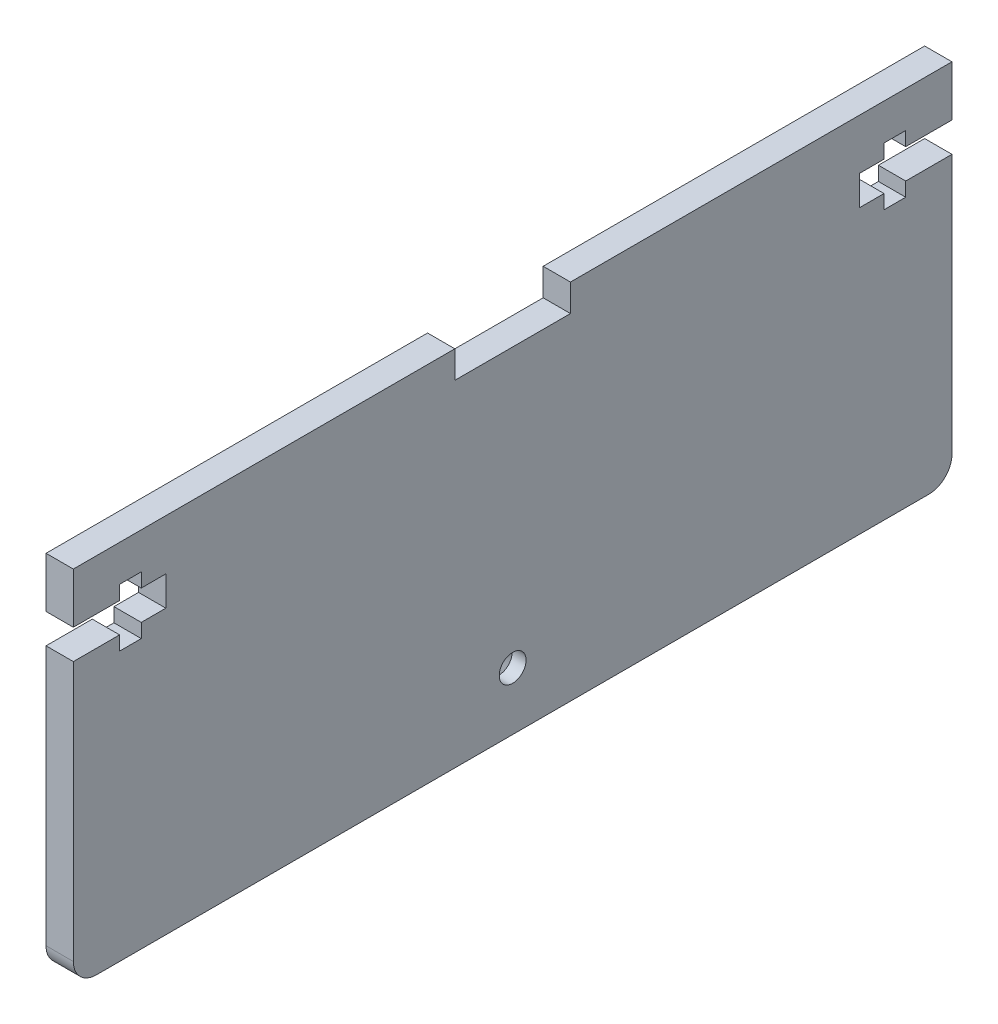
SolidWorks part; units mm, degrees
material "Acrylic (Medium-high impact)"
ref_plane "Front Plane" through (0, 0, 0) normal (0, 0, 1) x (1, 0, 0)
ref_plane "Top Plane" through (0, 0, 0) normal (0, 1, 0) x (1, 0, 0)
ref_plane "Right Plane" through (0, 0, 0) normal (1, 0, 0) x (0, 0, -1)
sketch "Sketch1" plane through (0, 0, 0) normal (1, 0, 0) x (0, 0, -1)
  line L1 (0, 0) -> (96.52, 0)
  line L2 (0, 0) -> (0, 39.878)
  line L3 (0, 39.878) -> (96.52, 39.878)
  line L4 (96.52, 0) -> (96.52, 39.878)
  dimension "D1" = 96.52
  dimension "D2" = 39.878
extrude "Boss-Extrude1" add sketch "Sketch1" along normal blind 3
hole_wizard "#32 (0.116) Diameter Hole1" positions "Sketch3" profile "Sketch2" hole size "#32" standard "ANSI Inch"
sketch "Sketch3" plane through (3, 0, 0) normal (1, 0, 0) x (0, 0, -1)
  line L0 (96.52, 39.878) -> (0, 39.878) construction
  line L1 (96.52, 0) -> (96.52, 39.878) construction
  point P0 (48.26, 6.35)
  dimension "D1" = 33.528
  dimension "D2" = 48.26
sketch "Sketch2" plane through (3, 6.35, -48.26) normal (0, 1, 0) x (0, 0, -1)
  line L0 (0, 0) -> (0, 2.4092)
  line L1 (0, 2.4092) -> (1.4732, 1.524)
  line L2 (1.4732, 1.524) -> (1.4732, 0)
  line L5 (1.4732, 0) -> (0, 0)
  line L10 (0, 2.4092) -> (-1.4732, 1.524) construction
  line L11 (0, -6.35) -> (0, 107.95) construction
  dimension "Hole Dia." = 2.9464
  dimension "Hole Depth" = 1.524
  dimension "Drill Angle" = 118
sketch "Sketch4" plane through (3, 0, 0) normal (1, 0, 0) x (0, 0, -1)
  line L0 (0, 34.338) -> (5.08, 34.338)
  line L1 (0, 39.878) -> (0, 0) construction
  line L2 (5.08, 34.338) -> (5.08, 35.8811)
  line L3 (5.08, 35.8811) -> (7.4613, 35.8811)
  line L4 (7.4613, 35.8811) -> (7.4613, 34.338)
  line L5 (7.4613, 34.338) -> (10.16, 34.338)
  line L6 (10.16, 34.338) -> (10.16, 31.0741)
  line L7 (10.16, 31.0741) -> (7.4613, 31.0741)
  line L8 (7.4613, 31.0741) -> (7.4613, 29.5311)
  line L9 (7.4613, 29.5311) -> (5.08, 29.5311)
  line L10 (5.08, 29.5311) -> (5.08, 31.0741)
  line L11 (5.08, 31.0741) -> (0, 31.0741)
  line L12 (0, 31.0741) -> (0, 34.338)
  line L13 (48.26, 39.878) -> (48.26, 0) construction
  line L14 (96.52, 39.878) -> (0, 39.878) construction
  line L15 (0, 0) -> (96.52, 0) construction
  line L16 (96.52, 31.0741) -> (96.52, 34.338)
  line L17 (91.44, 31.0741) -> (96.52, 31.0741)
  line L18 (91.44, 29.5311) -> (91.44, 31.0741)
  line L19 (89.0587, 29.5311) -> (91.44, 29.5311)
  line L20 (89.0587, 31.0741) -> (89.0587, 29.5311)
  line L21 (86.36, 31.0741) -> (89.0587, 31.0741)
  line L22 (86.36, 34.338) -> (86.36, 31.0741)
  line L23 (89.0587, 34.338) -> (86.36, 34.338)
  line L24 (89.0587, 35.8811) -> (89.0587, 34.338)
  line L25 (91.44, 35.8811) -> (89.0587, 35.8811)
  line L26 (91.44, 34.338) -> (91.44, 35.8811)
  line L27 (96.52, 34.338) -> (91.44, 34.338)
  dimension "D1" = 2.3813
  dimension "D2" = 3.2639
  dimension "D3" = 10.16
  dimension "D4" = 5.08
  dimension "D5" = 6.35
  dimension "D6" = 5.54
extrude "Cut-Extrude1" cut sketch "Sketch4" against normal blind 3
fillet "Fillet1" radius 2.54 2 edges at (1.5, 0, -96.52) (1.5, 0, 0)
sketch "Sketch5" plane through (3, 0, 0) normal (1, 0, 0) x (0, 0, -1)
  line L1 (96.52, 39.878) -> (0, 39.878) construction
  line L2 (41.91, 39.878) -> (54.61, 39.878)
  line L3 (41.91, 39.878) -> (41.91, 36.878)
  line L4 (41.91, 36.878) -> (54.61, 36.878)
  line L6 (54.61, 39.878) -> (54.61, 36.878)
  line L8 (96.52, 34.338) -> (96.52, 39.878) construction
  dimension "D1" = 12.7
  dimension "D2" = 3
  dimension "D3" = 41.91
extrude "Cut-Extrude2" cut sketch "Sketch5" against normal blind 3
sketch "Sketch7" plane through (3, 0, 0) normal (1, 0, 0) x (0, 0, -1)
sketch_block_instance "Block2-1"
sketch_block "Block2"
